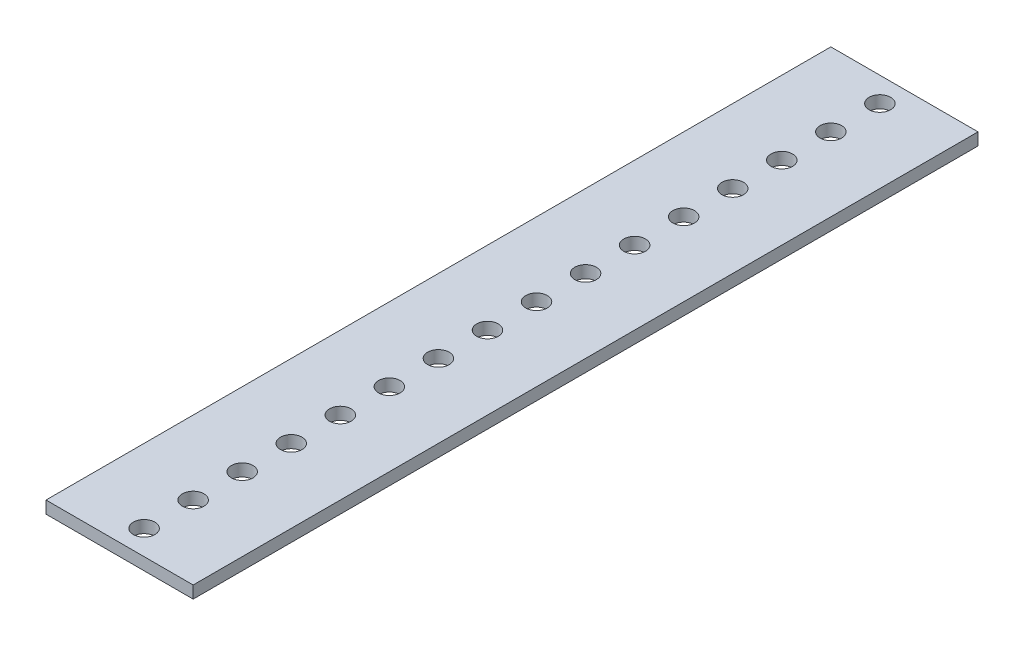
SolidWorks part; units mm, degrees
ref_plane "Front Plane" through (0, 0, 0) normal (0, 0, 1) x (1, 0, 0)
ref_plane "Top Plane" through (0, 0, 0) normal (0, 1, 0) x (1, 0, 0)
ref_plane "Right Plane" through (0, 0, 0) normal (1, 0, 0) x (0, 0, -1)
sketch "Sketch2" plane through (0, 0, 0) normal (0, 1, 0) x (1, 0, 0)
  line L1 (-19.05, -101.6) -> (19.05, -101.6)
  line L2 (-19.05, -101.6) -> (-19.05, 101.6)
  line L3 (-19.05, 101.6) -> (19.05, 101.6)
  line L4 (19.05, -101.6) -> (19.05, 101.6)
  line L5 (-19.05, -101.6) -> (19.05, 101.6) construction
  line L6 (-19.05, 101.6) -> (19.05, -101.6) construction
  point P0 (0, 0)
  dimension "D1" = 38.1
  dimension "D2" = 203.2
extrude "Boss-Extrude1" add sketch "Sketch2" along normal blind 3.175
sketch "Sketch3" plane through (0, 3.175, 0) normal (0, 1, 0) x (1, 0, 0)
  line L0 (-19.05, 101.6) -> (-19.05, -101.6) construction
  line L1 (-19.05, -101.6) -> (19.05, -101.6) construction
  circle A0 centre (0, -95.25) radius 2.794
  dimension "D1" = 19.05
  dimension "D2" = 6.35
extrude "Cut-Extrude1" cut sketch "Sketch3" against normal blind 3.175
pattern_linear "LPattern1" count 16 spacing 12.7 along (0, 0, -1) of "Cut-Extrude1"
